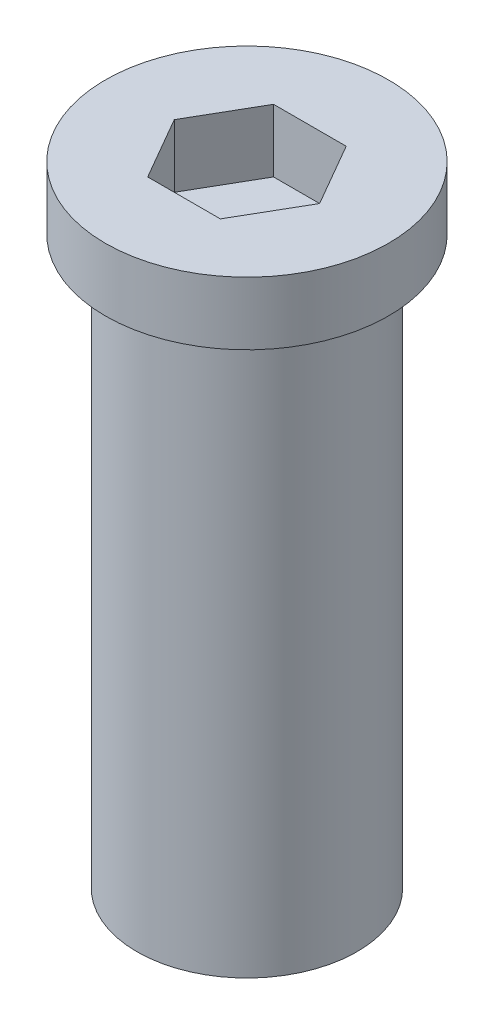
SolidWorks part; units mm, degrees
material "AISI 304"
ref_plane "Front Plane" through (0, 0, 0) normal (0, 0, 1) x (1, 0, 0)
ref_plane "Top Plane" through (0, 0, 0) normal (0, 1, 0) x (1, 0, 0)
ref_plane "Right Plane" through (0, 0, 0) normal (1, 0, 0) x (0, 0, -1)
sketch "Sketch1" plane through (0, 0, 0) normal (0, 1, 0) x (1, 0, 0)
  circle A0 centre (0, 0) radius 1.75
  dimension "D1" = 3.5
extrude "Boss-Extrude1" add sketch "Sketch1" along normal mid plane 9
sketch "Sketch2" plane through (0, 4.5, 0) normal (0, 1, 0) x (1, 0, 0)
  circle A0 centre (0, 0) radius 2.25
  dimension "D1" = 4.5
extrude "Boss-Extrude2" add sketch "Sketch2" along normal blind 1
sketch "Sketch3" plane through (0, 5.5, 0) normal (0, 1, 0) x (1, 0, 0)
  line L0 (1.1547, 0) -> (0.5774, 1)
  line L1 (0.5774, 1) -> (-0.5774, 1)
  line L2 (-0.5774, 1) -> (-1.1547, 0)
  line L3 (-1.1547, 0) -> (-0.5774, -1)
  line L4 (-0.5774, -1) -> (0.5774, -1)
  line L5 (0.5774, -1) -> (1.1547, 0)
  circle A0 centre (0, 0) radius 1 construction
  dimension "D1" = 2
  dimension "D2" = 1.1547
  dimension "D3" = 1.1547
  dimension "D4" = 1
  dimension "D5" = 1.1547
  dimension "D6" = 1.1547
  dimension "D7" = 2
  dimension "D8" = 2.3094
extrude "Cut-Extrude1" cut sketch "Sketch3" against normal blind 1
